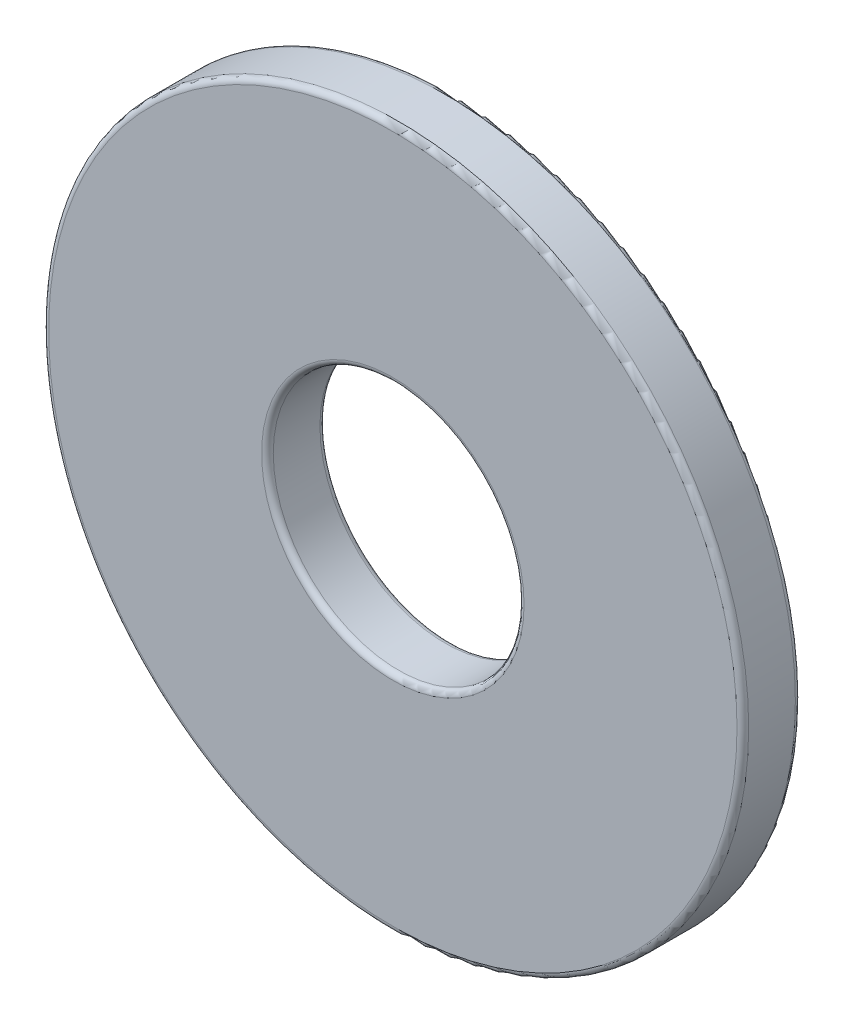
SolidWorks part; units mm, degrees
ref_plane "前视基准面" through (0, 0, 0) normal (0, 0, 1) x (1, 0, 0)
ref_plane "上视基准面" through (0, 0, 0) normal (0, 1, 0) x (1, 0, 0)
ref_plane "右视基准面" through (0, 0, 0) normal (1, 0, 0) x (0, 0, -1)
other "Configuration Table"
sketch "草图1" plane through (0, 0, 0) normal (0, 1, 0) x (1, 0, 0)
  line L0 (5.9, 0) -> (2.25, 0)
  line L1 (2.15, -0.1) -> (2.15, -0.9)
  line L2 (2.25, -1) -> (5.9, -1)
  line L3 (6, -0.9) -> (6, -0.1)
  line L4 (0, 0.0025) -> (0, -1.0025) construction
  arc A0 (6, -0.1) -> (5.9, 0) centre (5.9, -0.1) ccw
  arc A1 (2.25, 0) -> (2.15, -0.1) centre (2.25, -0.1) ccw
  arc A2 (2.15, -0.9) -> (2.25, -1) centre (2.25, -0.9) ccw
  arc A3 (5.9, -1) -> (6, -0.9) centre (5.9, -0.9) ccw
revolve "旋转1" add sketch "草图1" angle 360 about L4
